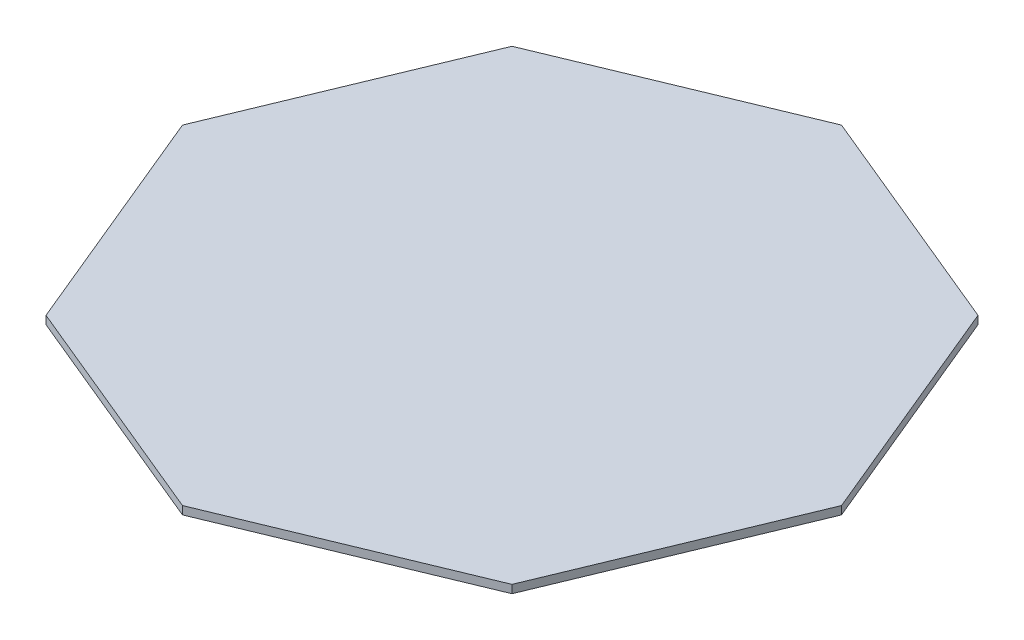
SolidWorks part; units mm, degrees
ref_plane "Front Plane" through (0, 0, 0) normal (0, 0, 1) x (1, 0, 0)
ref_plane "Top Plane" through (0, 0, 0) normal (0, 1, 0) x (1, 0, 0)
ref_plane "Right Plane" through (0, 0, 0) normal (1, 0, 0) x (0, 0, -1)
sketch "Sketch1" plane through (0, 0, 0) normal (0, 1, 0) x (1, 0, 0)
  line L1 (0, 81.1794) -> (-57.4025, 57.4025)
  line L2 (-57.4025, 57.4025) -> (-81.1794, 0)
  line L3 (-81.1794, 0) -> (-57.4025, -57.4025)
  line L4 (-57.4025, -57.4025) -> (0, -81.1794)
  line L5 (0, -81.1794) -> (57.4025, -57.4025)
  line L6 (57.4025, -57.4025) -> (81.1794, 0)
  line L7 (81.1794, 0) -> (57.4025, 57.4025)
  line L8 (57.4025, 57.4025) -> (0, 81.1794)
  circle A0 centre (0, 0) radius 75 construction
  dimension "D1" = 150
extrude "Boss-Extrude1" add sketch "Sketch1" along normal blind 2
ref_plane "Plane1" through (0, 0, 0) normal (-0.9239, 0, 0.3827) x (0.3827, 0, 0.9239)
ref_plane "Plane2" through (0, 0, 0) normal (-0.3827, 0, -0.9239) x (-0.9239, 0, 0.3827)
